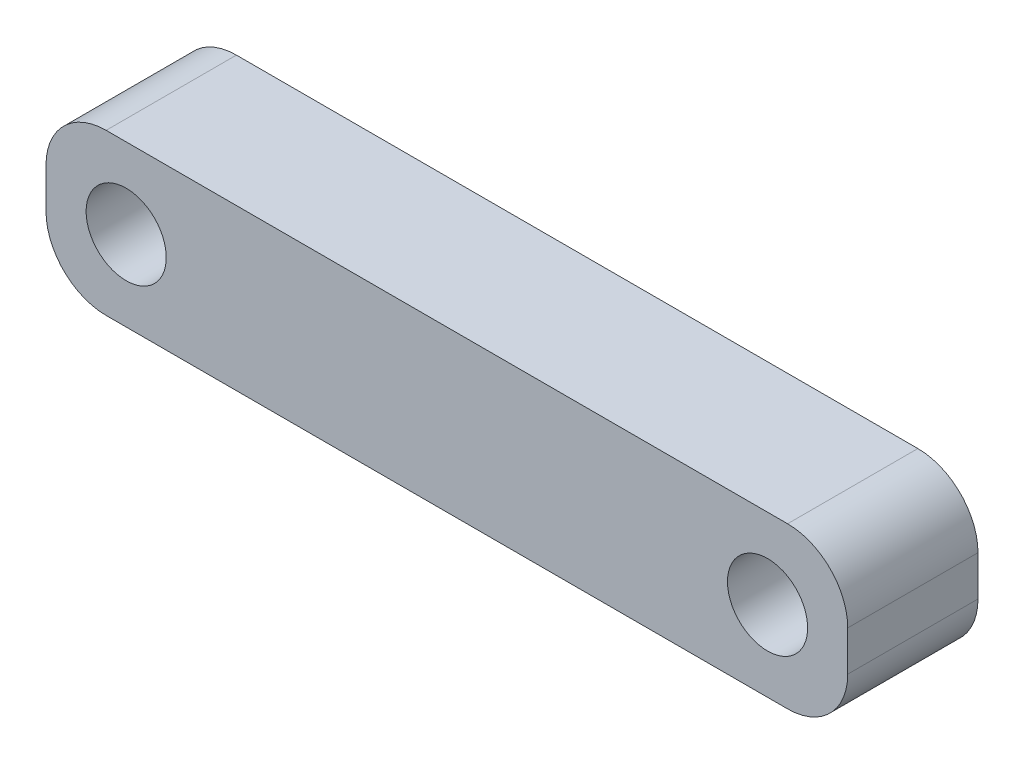
SolidWorks part; units mm, degrees
ref_plane "Plan de face" through (0, 0, 0) normal (0, 0, 1) x (1, 0, 0)
ref_plane "Plan de dessus" through (0, 0, 0) normal (0, 1, 0) x (1, 0, 0)
ref_plane "Plan de droite" through (0, 0, 0) normal (1, 0, 0) x (0, 0, -1)
sketch "Esquisse1" plane through (0, 0, 0) normal (0, 0, 1) x (1, 0, 0)
  line L0 (-32, 0) -> (0, 0) construction
  line L1 (-34, -8) -> (34, -8)
  line L2 (-40, -2) -> (-40, 2)
  line L3 (-34, 8) -> (34, 8)
  line L4 (40, -2) -> (40, 2)
  line L5 (-40, -8) -> (40, 8) construction
  line L6 (-40, 8) -> (40, -8) construction
  line L7 (0, 8) -> (0, -8) construction
  circle A0 centre (-32, 0) radius 4
  arc A1 (34, -8) -> (40, -2) centre (34, -2) ccw
  arc A2 (34, 8) -> (40, 2) centre (34, 2) cw
  arc A3 (-34, -8) -> (-40, -2) centre (-34, -2) cw
  arc A4 (-40, 2) -> (-34, 8) centre (-34, 2) cw
  circle A5 centre (32, 0) radius 4
  point P0 (0, 0)
  dimension "D3" = 6
  dimension "D5" = 8
  dimension "D1" = 16
  dimension "D2" = 80
  dimension "D4" = 8
extrude "Boss.-Extru.1" add sketch "Esquisse1" along normal blind 13
